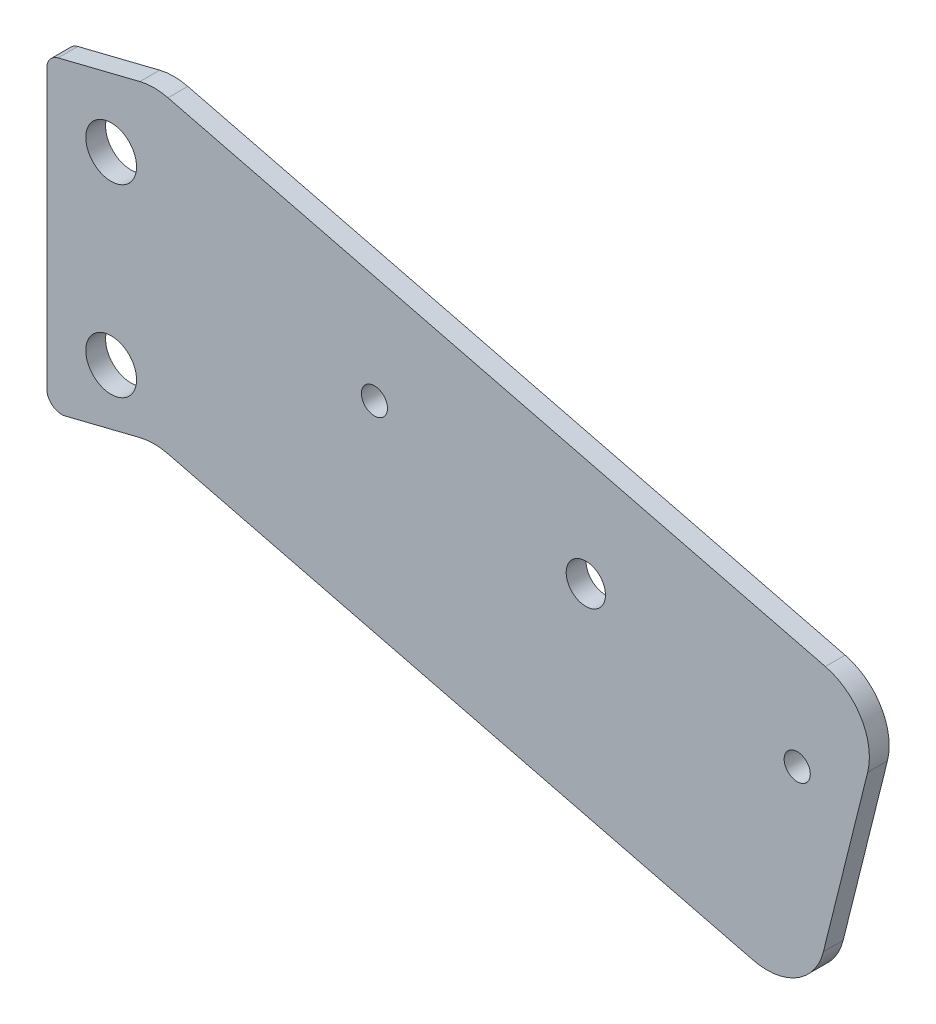
SolidWorks part; units mm, degrees
ref_plane "Front Plane" through (0, 0, 0) normal (0, 0, 1) x (1, 0, 0)
ref_plane "Top Plane" through (0, 0, 0) normal (0, 1, 0) x (1, 0, 0)
ref_plane "Right Plane" through (0, 0, 0) normal (1, 0, 0) x (0, 0, -1)
sketch "Sketch1" plane through (0, 0, 0) normal (0, 0, 1) x (1, 0, 0)
  line L0 (0, 0) -> (-82.5, -20.5696) construction
  line L1 (0, 0) -> (82.5, -20.5696) construction
  line L2 (-82.5, -20.5696) -> (82.5, -20.5696) construction
  line L3 (-82.5, -20.5696) -> (-74.3351, -53.317) construction
  line L4 (82.5, -20.5696) -> (74.3351, -53.317) construction
  line L5 (-74.3351, -53.317) -> (-37.949, -44.245) construction
  line L6 (-74.3351, -53.317) -> (-110.7212, -62.3891) construction
  line L7 (74.3351, -53.317) -> (37.949, -44.245) construction
  line L8 (74.3351, -53.317) -> (110.7212, -62.3891) construction
  line L9 (55, 0) -> (-55, 0) construction
  line L10 (-16.5133, -20.3494) -> (-2.4192, -16.8353)
  line L11 (2.4192, -16.8353) -> (115.561, -45.0447)
  line L12 (122.8447, -57.1669) -> (115.2242, -87.7312)
  line L13 (103.102, -95.015) -> (2.4192, -69.9119)
  line L14 (-2.4192, -69.9119) -> (-15.2843, -73.1196)
  line L16 (0, -20.5696) -> (0, -58.6696) construction
  line L17 (-7.366, -20.5696) -> (-7.366, -61.5696) construction
  line L18 (-18.4388, -22.8139) -> (-18.4388, -70.655)
  arc A0 (-2.4192, -16.8353) -> (2.4192, -16.8353) centre (0, -26.5383) cw
  arc A1 (2.4192, -69.9119) -> (-2.4192, -69.9119) centre (0, -79.6149) ccw
  arc A2 (115.561, -45.0447) -> (122.8447, -57.1669) centre (113.1417, -54.7477) cw
  arc A3 (115.2242, -87.7312) -> (103.102, -95.015) centre (105.5212, -85.312) cw
  arc A4 (-15.2843, -73.1196) -> (-18.4388, -70.655) centre (-15.8988, -70.655) cw
  arc A5 (-16.5133, -20.3494) -> (-18.4388, -22.8139) centre (-15.8988, -22.8139) ccw
  point P17 (-7.366, -29.8196)
  point P21 (0, -16.2322)
  point P24 (0, -69.3088)
  point P30 (-18.4388, -73.9061)
  point P38 (-18.4388, -20.8295)
  dimension "D13" = 10
  dimension "D7" = 2.54
  dimension "D1" = 165
  dimension "D2" = 18
  dimension "D3" = 152
  dimension "D4" = 33.75
  dimension "D5" = 33.75
  dimension "D6" = 16.51
  dimension "D8" = 37.5
  dimension "D9" = 37.5
  dimension "D10" = 33.5
  dimension "D12" = 48
  dimension "D14" = 7.366
  dimension "D15" = 41
  dimension "D16" = 31.75
extrude "Boss-Extrude1" add sketch "Sketch1" against normal blind 3.4036
hole_wizard "1/4 Clearance Hole1" positions "Sketch9" profile "Sketch10" hole size "1/4" standard "ANSI Inch" end condition through all
sketch "Sketch9" plane through (0, 0, 0) normal (0, 0, 1) x (1, 0, 0)
  point P3 (74.3351, -53.317)
sketch "Sketch10" plane through (74.3351, -53.317, 0) normal (1, 0, 0) x (0, -1, 0)
  line L0 (0, 0) -> (0, 3.4036)
  line L1 (0, 3.4036) -> (3.3782, 3.4036)
  line L2 (3.3782, 3.4036) -> (3.3782, 0)
  line L5 (3.3782, 0) -> (0, 0)
  line L11 (0, -6.35) -> (0, 107.95) construction
  dimension "Thru Hole Dia." = 6.7564
  dimension "Thru Hole Depth" = 3.4036
hole_wizard "M4 Clearance Hole1" positions "Sketch11" profile "Sketch12" hole size "M4" standard "ANSI Metric" end condition through all
sketch "Sketch11" plane through (0, 0, 0) normal (0, 0, 1) x (1, 0, 0)
  point P6 (37.949, -44.245)
  point P9 (110.7212, -62.3891)
sketch "Sketch12" plane through (37.949, -44.245, 0) normal (1, 0, 0) x (0, -1, 0)
  line L0 (0, 0) -> (0, 3.4036)
  line L1 (0, 3.4036) -> (2.25, 3.4036)
  line L2 (2.25, 3.4036) -> (2.25, 0)
  line L5 (2.25, 0) -> (0, 0)
  line L11 (0, -6.35) -> (0, 107.95) construction
  dimension "Thru Hole Dia." = 4.5
  dimension "Thru Hole Depth" = 3.4036
hole_wizard "Hole for 1/4 300® SC Nuts (SP)1" positions "Sketch13" profile "Sketch14" hole size "1/4-20" standard "PEM® Inch" end condition through all
sketch "Sketch13" plane through (0, 0, 0) normal (0, 0, 1) x (1, 0, 0)
  point P20 (-7.366, -61.5696)
  point P23 (-7.366, -29.8196)
sketch "Sketch14" plane through (-7.366, -61.5696, 0) normal (1, 0, 0) x (0, -1, 0)
  line L0 (0, 0) -> (0, 3.4036)
  line L1 (0, 3.4036) -> (4.3688, 3.4036)
  line L2 (4.3688, 3.4036) -> (4.3688, 0)
  line L5 (4.3688, 0) -> (0, 0)
  line L11 (0, -6.35) -> (0, 107.95) construction
  dimension "Thru Hole Dia." = 8.7376
  dimension "Thru Hole Depth" = 3.4036
